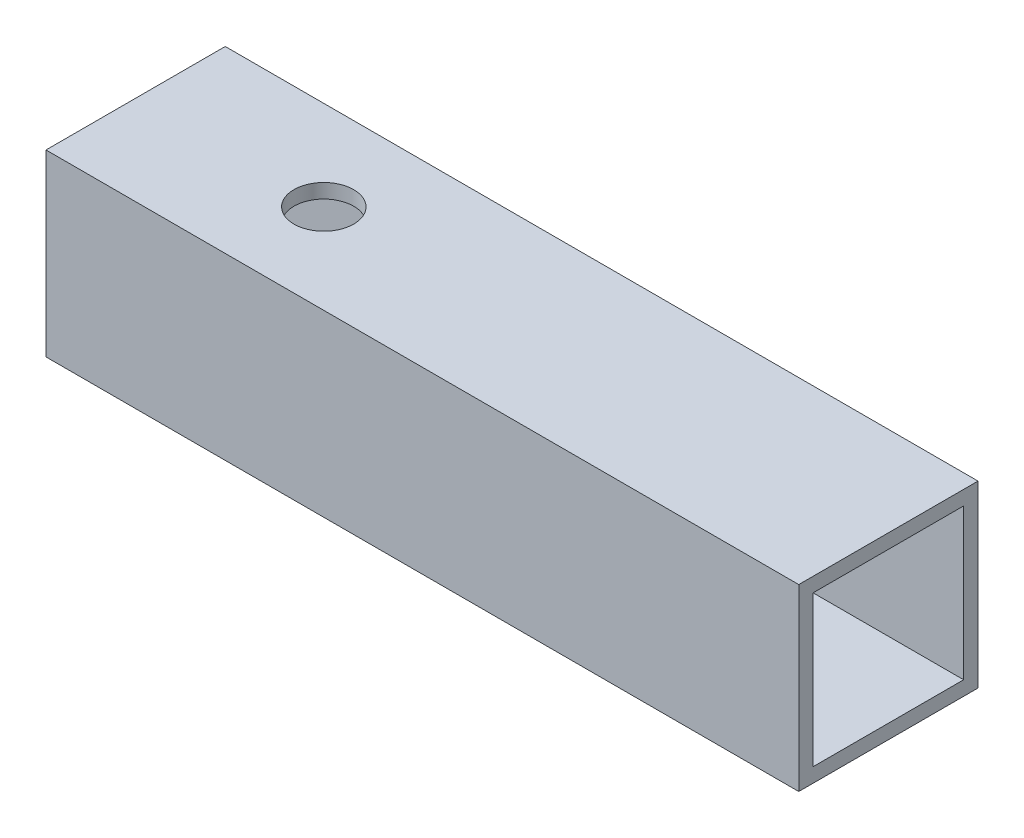
SolidWorks part; units mm, degrees
material "Brass"
ref_plane "Front Plane" through (0, 0, 0) normal (0, 0, 1) x (1, 0, 0)
ref_plane "Top Plane" through (0, 0, 0) normal (0, 1, 0) x (1, 0, 0)
ref_plane "Right Plane" through (0, 0, 0) normal (1, 0, 0) x (0, 0, -1)
sketch "Sketch1" plane through (0, 0, 0) normal (1, 0, 0) x (0, 0, -1)
  line L1 (-2.3813, 2.3812) -> (2.3812, 2.3812)
  line L2 (-2.3813, 2.3812) -> (-2.3813, -2.3812)
  line L3 (-2.3813, -2.3812) -> (2.3812, -2.3812)
  line L4 (2.3812, 2.3812) -> (2.3812, -2.3812)
  line L5 (-2.3813, 2.3812) -> (2.3812, -2.3812) construction
  line L6 (-2.3813, -2.3812) -> (2.3812, 2.3812) construction
  point P0 (0, 0)
  dimension "D1" = 4.7625
  dimension "D2" = 4.7625
extrude "Boss-Extrude1" add sketch "Sketch1" along normal blind 20
sketch "Sketch2" plane through (0, 0, 0) normal (-1, 0, 0) x (0, 0, 1)
  line L1 (-2, 2) -> (2, 2)
  line L2 (-2, 2) -> (-2, -2)
  line L3 (-2, -2) -> (2, -2)
  line L4 (2, 2) -> (2, -2)
  line L5 (-2, 2) -> (2, -2) construction
  line L6 (-2, -2) -> (2, 2) construction
  point P0 (0, 0)
  dimension "D1" = 4
  dimension "D2" = 4
extrude "Cut-Extrude1" cut sketch "Sketch2" against normal through all
sketch "Sketch3" plane through (0, 2.3812, 0) normal (0, 1, 0) x (1, 0, 0)
  line L0 (20, 2.3812) -> (20, -2.3813) construction
  line L1 (0, 2.3812) -> (0, -2.3813) construction
  circle A0 centre (5, 0) radius 0.7937
  point P4 (20, 0)
  dimension "D1" = 1.5875
  dimension "D2" = 5
extrude "Cut-Extrude2" cut sketch "Sketch3" against normal blind 10
